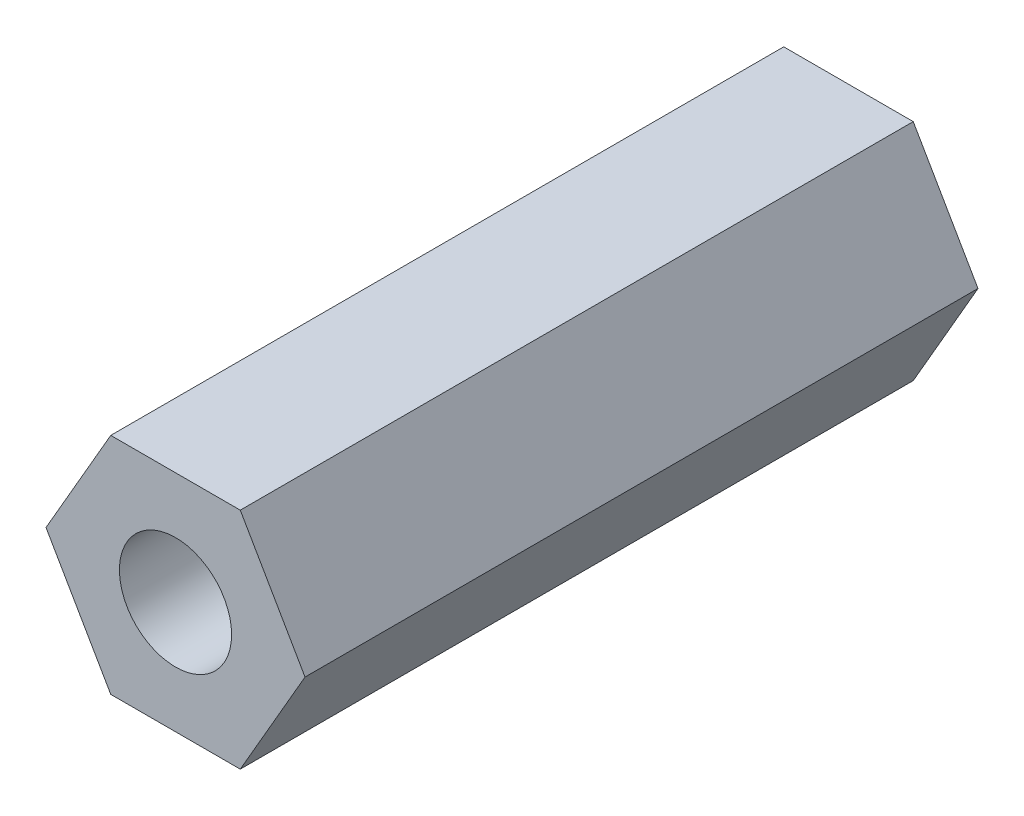
SolidWorks part; units mm, degrees
ref_plane "Front Plane" through (0, 0, 0) normal (0, 0, 1) x (1, 0, 0)
ref_plane "Top Plane" through (0, 0, 0) normal (0, 1, 0) x (1, 0, 0)
ref_plane "Right Plane" through (0, 0, 0) normal (1, 0, 0) x (0, 0, -1)
sketch "Sketch1" plane through (0, 0, 0) normal (0, 0, 1) x (1, 0, 0)
  line L1 (-5.7735, 0) -> (-2.8868, -5)
  line L2 (-2.8868, -5) -> (2.8868, -5)
  line L3 (2.8868, -5) -> (5.7735, 0)
  line L4 (5.7735, 0) -> (2.8868, 5)
  line L5 (2.8868, 5) -> (-2.8868, 5)
  line L6 (-2.8868, 5) -> (-5.7735, 0)
  circle A0 centre (0, 0) radius 5 construction
  dimension "D1" = 10
extrude "Boss-Extrude1" add sketch "Sketch1" along normal up to surface (30 mm away)
sketch "Sketch2" plane through (0, 0, 30) normal (0, 0, 1) x (1, 0, 0)
  circle A0 centre (0, 0) radius 2.5
  dimension "D1" = 5
extrude "Cut-Extrude1" cut sketch "Sketch2" against normal blind 20
ref_plane "Plane1" through (0, 0, 15) normal (0, 0, 1) x (1, 0, 0)
mirror "Mirror1" about plane through (0, 0, 15) normal (0, 0, 1) of "Cut-Extrude1"
